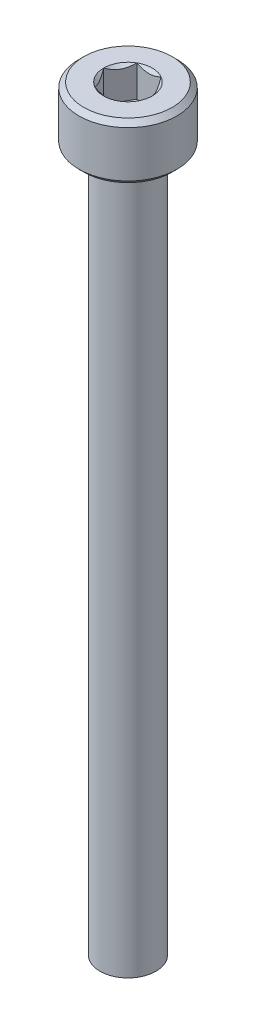
SolidWorks part; units mm, degrees
ref_plane "Front" through (0, 0, 0) normal (0, 0, 1) x (1, 0, 0)
ref_plane "Top" through (0, 0, 0) normal (0, 1, 0) x (1, 0, 0)
ref_plane "Right" through (0, 0, 0) normal (1, 0, 0) x (0, 0, -1)
sketch "Sketch1" plane through (0, 0, 0) normal (0, 1, 0) x (1, 0, 0)
  circle A0 centre (0, 0) radius 3.5
  dimension "D1" = 7
extrude "Boss-Extrude1" add sketch "Sketch1" along normal blind 4
sketch "Sketch2" plane through (0, 4, 0) normal (0, 1, 0) x (1, 0, 0)
  line L1 (0.866, 1.5) -> (-0.866, 1.5)
  line L2 (-0.866, 1.5) -> (-1.7321, 0)
  line L3 (-1.7321, 0) -> (-0.866, -1.5)
  line L4 (-0.866, -1.5) -> (0.866, -1.5)
  line L5 (0.866, -1.5) -> (1.7321, 0)
  line L6 (1.7321, 0) -> (0.866, 1.5)
  circle A0 centre (0, 0) radius 1.5 construction
  point P10 (0, 1.5)
  dimension "D1" = 3
extrude "Cut-Extrude1" cut sketch "Sketch2" against normal blind 2.25
sketch "Sketch3" plane through (0, 4, 0) normal (0, 1, 0) x (1, 0, 0)
  circle A0 centre (0, 0) radius 1.7321
extrude "Cut-Extrude2" cut sketch "Sketch3" against normal through all draft 45
chamfer "Chamfer1" distance 0.35 angle 45 2 edges at (0, 0, 3.5) (0, 4, 3.5)
sketch "草图1" plane through (0, 0, 0) normal (0, -1, 0) x (-1, 0, 0)
  circle A0 centre (0, 0) radius 2
  dimension "D1" = 4
extrude "凸台-拉伸1" add sketch "草图1" along normal blind 50
